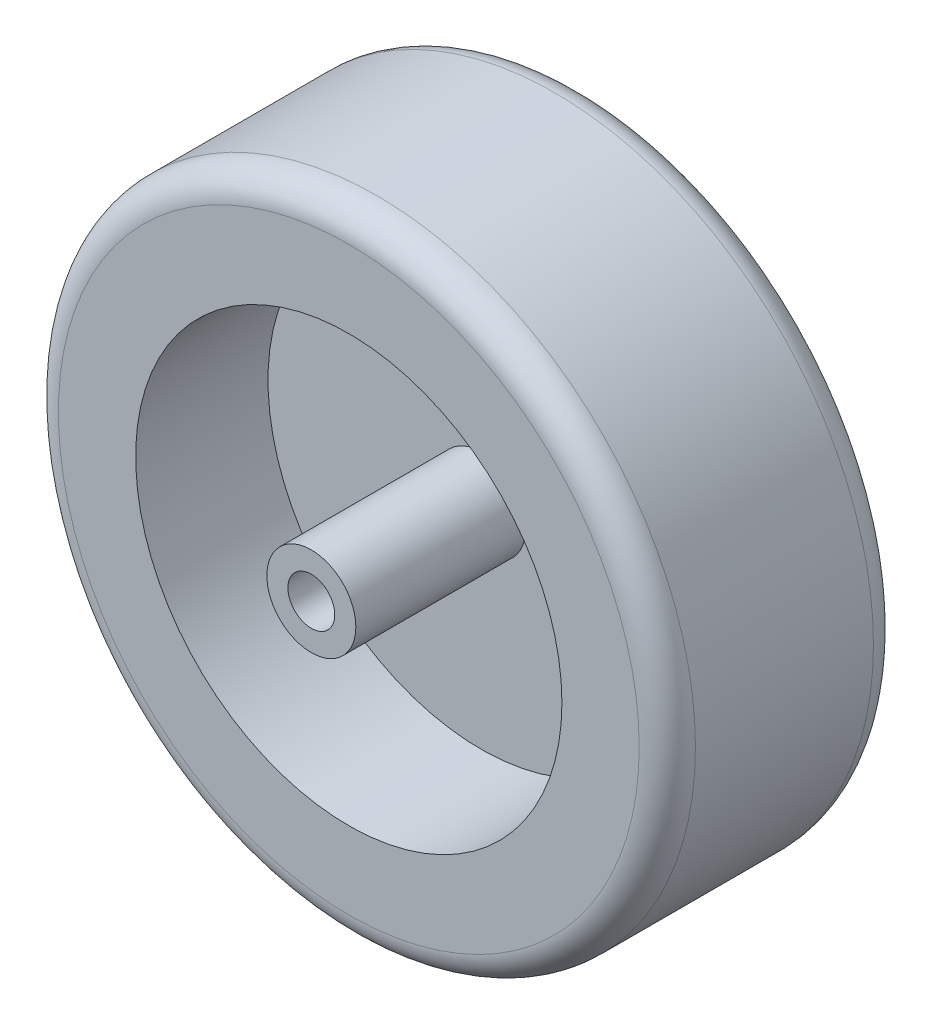
SolidWorks part; units mm, degrees
ref_plane "Front" through (0, 0, 0) normal (0, 0, 1) x (1, 0, 0)
ref_plane "Top" through (0, 0, 0) normal (0, 1, 0) x (1, 0, 0)
ref_plane "Right" through (0, 0, 0) normal (1, 0, 0) x (0, 0, -1)
sketch "Sketch1" plane through (0, 0, 0) normal (0, 1, 0) x (1, 0, 0)
  line L0 (0, 0) -> (0, 29)
  line L1 (0, 29) -> (34, 29)
  line L2 (34, 29) -> (34, 4)
  line L3 (34, 4) -> (22.75, 4)
  line L4 (22.75, 4) -> (22.75, 18.125)
  line L5 (22.75, 18.125) -> (4.75, 18.125)
  line L6 (4.75, 18.125) -> (4.75, 0)
  line L7 (4.75, 0) -> (0, 0)
  dimension "D1" = 29
  dimension "D2" = 34
  dimension "D3" = 25
  dimension "D4" = 4.75
  dimension "D5" = 18
revolve "Revolve1" add sketch "Sketch1" angle 360 about L0
fillet "Fillet1" radius 3 2 edges at (34, 0, -4) (34, 0, -29)
sketch "Sketch2" plane through (0, 0, 0) normal (0, 0, 1) x (1, 0, 0)
  circle A0 centre (0, 0) radius 2.5
  dimension "D1" = 5
extrude "Cut-Extrude1" cut sketch "Sketch2" against normal blind 10
